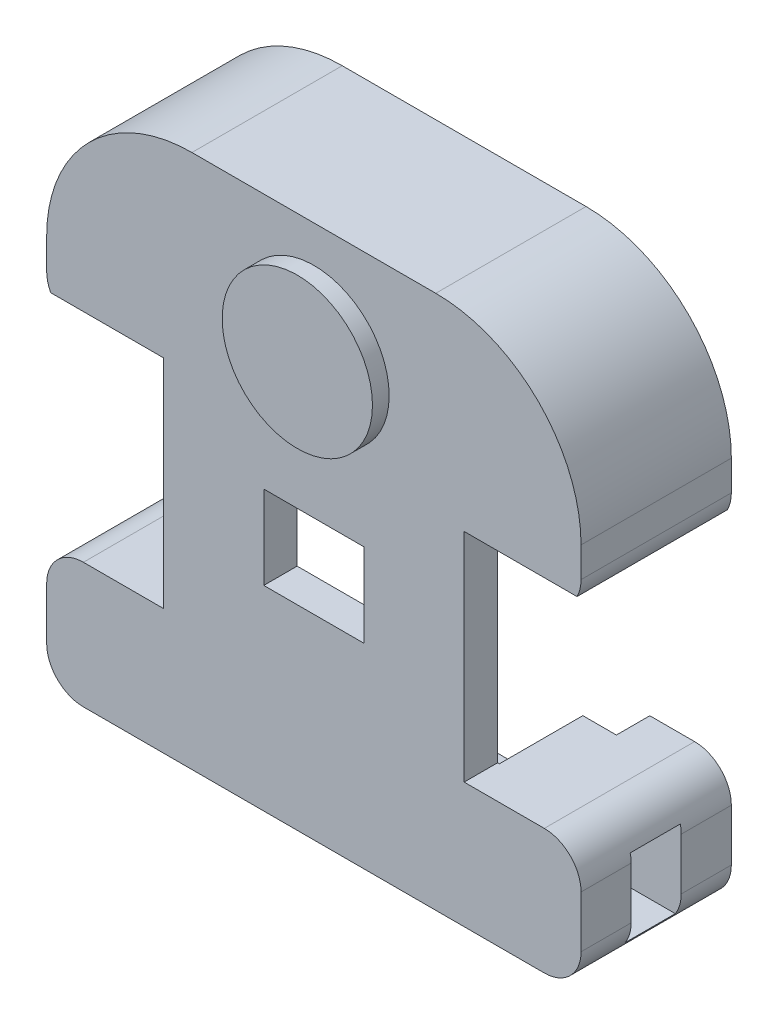
SolidWorks part; units mm, degrees
ref_plane "Front Plane" through (0, 0, 0) normal (0, 0, 1) x (1, 0, 0)
ref_plane "Top Plane" through (0, 0, 0) normal (0, 1, 0) x (1, 0, 0)
ref_plane "Right Plane" through (0, 0, 0) normal (1, 0, 0) x (0, 0, -1)
ref_plane "Plane1" through (0, 0, 2.54) normal (0, 0, 1) x (1, 0, 0)
sketch "Sketch1" plane through (0, 0, 2.54) normal (0, 0, 1) x (1, 0, 0)
  line L0 (-35.052, 0) -> (35.052, 0)
  line L1 (38.1, 3.048) -> (38.1, 10.922)
  line L2 (35.052, 13.97) -> (31.242, 13.97)
  line L3 (28.194, 17.018) -> (28.194, 45.974)
  line L4 (31.242, 49.022) -> (35.052, 49.022)
  line L5 (38.1, 52.07) -> (38.1, 56.642)
  line L6 (18.542, 76.2) -> (-18.542, 76.2)
  line L7 (-38.1, 56.642) -> (-38.1, 52.07)
  line L8 (-35.052, 49.022) -> (-31.242, 49.022)
  line L9 (-28.194, 45.974) -> (-28.194, 17.018)
  line L10 (-31.242, 13.97) -> (-35.052, 13.97)
  line L11 (-38.1, 10.922) -> (-38.1, 3.048)
  arc A0 (35.052, 49.022) -> (38.1, 52.07) centre (35.052, 52.07) ccw
  arc A1 (-38.1, 52.07) -> (-35.052, 49.022) centre (-35.052, 52.07) ccw
  arc A2 (-31.242, 49.022) -> (-28.194, 45.974) centre (-31.242, 45.974) cw
  arc A3 (28.194, 45.974) -> (31.242, 49.022) centre (31.242, 45.974) cw
  arc A4 (38.1, 10.922) -> (35.052, 13.97) centre (35.052, 10.922) ccw
  arc A5 (31.242, 13.97) -> (28.194, 17.018) centre (31.242, 17.018) cw
  arc A6 (-28.194, 17.018) -> (-31.242, 13.97) centre (-31.242, 17.018) cw
  arc A7 (-35.052, 13.97) -> (-38.1, 10.922) centre (-35.052, 10.922) ccw
  arc A8 (-35.052, 0) -> (-38.1, 3.048) centre (-35.052, 3.048) cw
  arc A9 (35.052, 0) -> (38.1, 3.048) centre (35.052, 3.048) ccw
  arc A10 (-18.542, 76.2) -> (-38.1, 56.642) centre (-18.542, 56.642) ccw
  arc A11 (38.1, 56.642) -> (18.542, 76.2) centre (18.542, 56.642) ccw
  dimension "D1" = 3.048
  dimension "D4" = 76.2
  dimension "D5" = 76.2
  dimension "D6" = 28.956
  dimension "D7" = 7.874
  dimension "D8" = 9.906
  dimension "D2" = 19.558
extrude "Boss-Extrude1" add sketch "Sketch1" against normal blind 17.78
sketch "Sketch2" plane through (0, 0, -15.24) normal (0, 0, -1) x (-1, 0, 0)
  line L12 (33.02, 54.102) -> (33.02, 56.642)
  line L13 (33.02, 54.102) -> (33.02, 56.642)
  line L14 (-33.02, 56.642) -> (-33.02, 54.102)
  line L15 (-33.02, 56.642) -> (-33.02, 54.102)
  line L24 (-33.02, 54.102) -> (-31.242, 54.102)
  line L25 (-23.114, 45.974) -> (-23.114, 17.018)
  line L26 (-31.242, 8.89) -> (-33.02, 8.89)
  line L27 (-33.02, 8.89) -> (-33.02, 5.08)
  line L28 (-33.02, 5.08) -> (33.02, 5.08)
  line L29 (33.02, 5.08) -> (33.02, 8.89)
  line L30 (33.02, 8.89) -> (31.242, 8.89)
  line L31 (23.114, 17.018) -> (23.114, 45.974)
  line L32 (31.242, 54.102) -> (33.02, 54.102)
  line L34 (18.542, 71.12) -> (-18.542, 71.12)
  line L36 (-33.02, 54.102) -> (-31.242, 54.102)
  line L37 (-23.114, 45.974) -> (-23.114, 17.018)
  line L38 (-31.242, 8.89) -> (-33.02, 8.89)
  line L39 (-33.02, 8.89) -> (-33.02, 5.08)
  line L40 (-33.02, 5.08) -> (33.02, 5.08)
  line L41 (33.02, 5.08) -> (33.02, 8.89)
  line L42 (33.02, 8.89) -> (31.242, 8.89)
  line L43 (23.114, 17.018) -> (23.114, 45.974)
  line L44 (31.242, 54.102) -> (33.02, 54.102)
  line L46 (18.542, 71.12) -> (-18.542, 71.12)
  arc A24 (-23.114, 45.974) -> (-31.242, 54.102) centre (-31.242, 45.974) ccw
  arc A25 (-31.242, 8.89) -> (-23.114, 17.018) centre (-31.242, 17.018) ccw
  arc A26 (23.114, 17.018) -> (31.242, 8.89) centre (31.242, 17.018) ccw
  arc A27 (31.242, 54.102) -> (23.114, 45.974) centre (31.242, 45.974) ccw
  arc A28 (33.02, 56.642) -> (18.542, 71.12) centre (18.542, 56.642) ccw
  arc A29 (-18.542, 71.12) -> (-33.02, 56.642) centre (-18.542, 56.642) ccw
  arc A30 (-23.114, 45.974) -> (-31.242, 54.102) centre (-31.242, 45.974) ccw
  arc A31 (-31.242, 8.89) -> (-23.114, 17.018) centre (-31.242, 17.018) ccw
  arc A32 (23.114, 17.018) -> (31.242, 8.89) centre (31.242, 17.018) ccw
  arc A33 (31.242, 54.102) -> (23.114, 45.974) centre (31.242, 45.974) ccw
  arc A34 (33.02, 56.642) -> (18.542, 71.12) centre (18.542, 56.642) ccw
  arc A35 (-18.542, 71.12) -> (-33.02, 56.642) centre (-18.542, 56.642) ccw
  dimension "D1" = 5.08
extrude "Cut-Extrude1" cut sketch "Sketch2" against normal blind 12.7
sketch "Sketch7" plane through (0, 0, -15.24) normal (0, 0, -1) x (-1, 0, 0)
  line L24 (-35.052, 46.482) -> (-31.242, 46.482)
  line L25 (-30.734, 45.974) -> (-30.734, 17.018)
  line L26 (-31.242, 16.51) -> (-35.052, 16.51)
  line L27 (-40.64, 10.922) -> (-40.64, 3.048)
  line L28 (-35.052, -2.54) -> (35.052, -2.54)
  line L29 (40.64, 3.048) -> (40.64, 10.922)
  line L30 (35.052, 16.51) -> (31.242, 16.51)
  line L31 (30.734, 17.018) -> (30.734, 45.974)
  line L32 (31.242, 46.482) -> (35.052, 46.482)
  line L33 (40.64, 52.07) -> (40.64, 56.642)
  line L34 (18.542, 78.74) -> (-18.542, 78.74)
  line L35 (-40.64, 56.642) -> (-40.64, 52.07)
  line L36 (-35.052, 46.482) -> (-31.242, 46.482)
  line L37 (-30.734, 45.974) -> (-30.734, 17.018)
  line L38 (-31.242, 16.51) -> (-35.052, 16.51)
  line L39 (-40.64, 10.922) -> (-40.64, 3.048)
  line L40 (-35.052, -2.54) -> (35.052, -2.54)
  line L41 (40.64, 3.048) -> (40.64, 10.922)
  line L42 (35.052, 16.51) -> (31.242, 16.51)
  line L43 (30.734, 17.018) -> (30.734, 45.974)
  line L44 (31.242, 46.482) -> (35.052, 46.482)
  line L45 (40.64, 52.07) -> (40.64, 56.642)
  line L46 (18.542, 78.74) -> (-18.542, 78.74)
  line L47 (-40.64, 56.642) -> (-40.64, 52.07)
  arc A12 (40.64, 56.642) -> (18.542, 78.74) centre (18.542, 56.642) ccw
  arc A13 (40.64, 56.642) -> (18.542, 78.74) centre (18.542, 56.642) ccw
  arc A18 (-18.542, 78.74) -> (-40.64, 56.642) centre (-18.542, 56.642) ccw
  arc A19 (-18.542, 78.74) -> (-40.64, 56.642) centre (-18.542, 56.642) ccw
  arc A24 (-40.64, 52.07) -> (-35.052, 46.482) centre (-35.052, 52.07) ccw
  arc A25 (-30.734, 45.974) -> (-31.242, 46.482) centre (-31.242, 45.974) ccw
  arc A26 (-31.242, 16.51) -> (-30.734, 17.018) centre (-31.242, 17.018) ccw
  arc A27 (-35.052, 16.51) -> (-40.64, 10.922) centre (-35.052, 10.922) ccw
  arc A28 (-40.64, 3.048) -> (-35.052, -2.54) centre (-35.052, 3.048) ccw
  arc A29 (35.052, -2.54) -> (40.64, 3.048) centre (35.052, 3.048) ccw
  arc A30 (40.64, 10.922) -> (35.052, 16.51) centre (35.052, 10.922) ccw
  arc A31 (30.734, 17.018) -> (31.242, 16.51) centre (31.242, 17.018) ccw
  arc A32 (31.242, 46.482) -> (30.734, 45.974) centre (31.242, 45.974) ccw
  arc A33 (35.052, 46.482) -> (40.64, 52.07) centre (35.052, 52.07) ccw
  arc A36 (-40.64, 52.07) -> (-35.052, 46.482) centre (-35.052, 52.07) ccw
  arc A37 (-30.734, 45.974) -> (-31.242, 46.482) centre (-31.242, 45.974) ccw
  arc A38 (-31.242, 16.51) -> (-30.734, 17.018) centre (-31.242, 17.018) ccw
  arc A39 (-35.052, 16.51) -> (-40.64, 10.922) centre (-35.052, 10.922) ccw
  arc A40 (-40.64, 3.048) -> (-35.052, -2.54) centre (-35.052, 3.048) ccw
  arc A41 (35.052, -2.54) -> (40.64, 3.048) centre (35.052, 3.048) ccw
  arc A42 (40.64, 10.922) -> (35.052, 16.51) centre (35.052, 10.922) ccw
  arc A43 (30.734, 17.018) -> (31.242, 16.51) centre (31.242, 17.018) ccw
  arc A44 (31.242, 46.482) -> (30.734, 45.974) centre (31.242, 45.974) ccw
  arc A45 (35.052, 46.482) -> (40.64, 52.07) centre (35.052, 52.07) ccw
  arc M47 (-38.1, 52.07) -> (-35.052, 49.022) centre (-35.052, 52.07) ccw
  line M48 (-35.052, 49.022) -> (-31.242, 49.022)
  arc M49 (-31.242, 49.022) -> (-28.194, 45.974) centre (-31.242, 45.974) cw
  line M50 (-28.194, 45.974) -> (-28.194, 17.018)
  arc M51 (-28.194, 17.018) -> (-31.242, 13.97) centre (-31.242, 17.018) cw
  line M52 (-31.242, 13.97) -> (-35.052, 13.97)
  arc M53 (-35.052, 13.97) -> (-38.1, 10.922) centre (-35.052, 10.922) ccw
  line M54 (-38.1, 10.922) -> (-38.1, 3.048)
  arc M55 (-38.1, 3.048) -> (-35.052, 0) centre (-35.052, 3.048) ccw
  line M56 (-35.052, 0) -> (35.052, 0)
  arc M57 (35.052, 0) -> (38.1, 3.048) centre (35.052, 3.048) ccw
  line M58 (38.1, 3.048) -> (38.1, 10.922)
  arc M59 (38.1, 10.922) -> (35.052, 13.97) centre (35.052, 10.922) ccw
  line M60 (35.052, 13.97) -> (31.242, 13.97)
  arc M61 (31.242, 13.97) -> (28.194, 17.018) centre (31.242, 17.018) cw
  line M62 (28.194, 17.018) -> (28.194, 45.974)
  arc M63 (28.194, 45.974) -> (31.242, 49.022) centre (31.242, 45.974) cw
  line M64 (31.242, 49.022) -> (35.052, 49.022)
  arc M65 (35.052, 49.022) -> (38.1, 52.07) centre (35.052, 52.07) ccw
  line M66 (38.1, 52.07) -> (38.1, 56.642)
  arc M67 (38.1, 56.642) -> (18.542, 76.2) centre (18.542, 56.642) ccw
  line M68 (18.542, 76.2) -> (-18.542, 76.2)
  arc M69 (-18.542, 76.2) -> (-38.1, 56.642) centre (-18.542, 56.642) ccw
  line M70 (-38.1, 56.642) -> (-38.1, 52.07)
  dimension "D1" = 2.54
extrude "Boss-Extrude2" add sketch "Sketch7" along normal blind 5.08 and the other way up to surface (17.78 mm away) contours L46 A19 L47 A36 L36 A37 L37 A38 L38 A39 L39 A40 L40 A41 L41 A42 L42 A43 L43 A44 L44 A45 L45 A13 M47 M70 M69 M68 M67 M66 M65 M64 M63 M62 M61 M60 M59 M58 M57 M56 M55 M54 M53 M52 M51 M50 M49 M48 other way up to face at (0, 32.6064, 2.54)
sketch "Sketch8" plane through (0, 0, -20.32) normal (0, 0, -1) x (-1, 0, 0)
  line L9 (-22.86, 49.53) -> (-22.86, 16.51)
  line L18 (-22.86, 49.53) -> (-46.482, 49.53)
  line L19 (-46.482, 49.53) -> (-46.482, 16.51)
  line L20 (-46.482, 16.51) -> (-22.86, 16.51)
  line L27 (0, 41.91) -> (0, -41.91) construction
  line L28 (46.482, 16.51) -> (22.86, 16.51)
  line L30 (22.86, 49.53) -> (22.86, 16.51)
  line L31 (22.86, 49.53) -> (46.482, 49.53)
  line L32 (46.482, 49.53) -> (46.482, 16.51)
  line L33 (-38.1, 10.922) -> (-38.1, 3.048) construction
  line L34 (-35.052, 0) -> (35.052, 0) construction
  dimension "D1" = 23.622
  dimension "D2" = 33.02
  dimension "D3" = 15.24
  dimension "D4" = 16.51
extrude "Cut-Extrude2" cut sketch "Sketch8" against normal up to surface (22.86 mm away) up to face at (0, 32.6064, 2.54)
sketch "Sketch9" plane through (-40.64, 0, 0) normal (-1, 0, 0) x (0, 0, 1)
  line L0 (-12.7, 12.192) -> (-12.7, 0)
  line L1 (-12.7, 0) -> (-5.08, 0)
  line L2 (-5.08, 0) -> (-5.08, 12.192)
  line L3 (-5.08, 12.192) -> (-12.7, 12.192)
  line L4 (2.54, 0) -> (2.54, 3.048) construction
  point P7 (2.54, 1.524)
  dimension "D1" = 12.192
  dimension "D2" = 7.62
  dimension "D3" = 7.62
extrude "Cut-Extrude3" cut sketch "Sketch9" against normal up to surface (81.28 mm away) up to face at (40.64, 6.985, -8.89)
sketch "Sketch10" plane through (0, 0, 2.54) normal (0, 0, 1) x (1, 0, 0)
  line L0 (-7.62, 39.878) -> (7.62, 39.878)
  line L1 (7.62, 39.878) -> (7.62, 27.178)
  line L2 (7.62, 27.178) -> (-7.62, 27.178)
  line L3 (-7.62, 27.178) -> (-7.62, 39.878)
  line L4 (-22.86, 49.53) -> (-22.86, 16.51) construction
  dimension "D1" = 12.7
  dimension "D2" = 15.24
  dimension "D3" = 27.178
  dimension "D4" = 15.24
extrude "Cut-Extrude4" cut sketch "Sketch10" against normal up to surface (5.08 mm away) up to face at (0, 35.7588, -2.54)
sketch "Sketch11" plane through (0, 0, 2.54) normal (0, 0, 1) x (1, 0, 0)
  circle A0 centre (0.0244, 61.722) radius 11.43
  point P2 (0, 63.1484)
  point P3 (0, 61.8324)
  point P6 (0, 0)
  dimension "D1" = 22.86
  dimension "D2" = 40.005
  dimension "D3" = 12.192
extrude "Boss-Extrude3" add sketch "Sketch11" along normal blind 2.54
